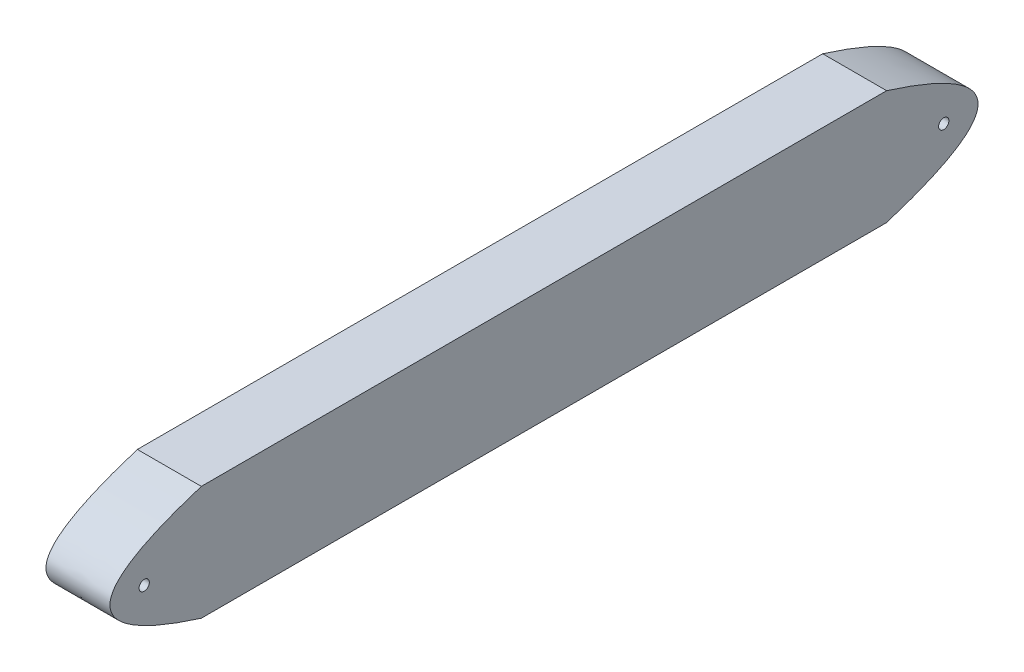
SolidWorks part; units mm, degrees
ref_plane "Front Plane" through (0, 0, 0) normal (0, 0, 1) x (1, 0, 0)
ref_plane "Top Plane" through (0, 0, 0) normal (0, 1, 0) x (1, 0, 0)
ref_plane "Right Plane" through (0, 0, 0) normal (1, 0, 0) x (0, 0, -1)
sketch "Sketch1" plane through (0, 0, 0) normal (1, 0, 0) x (0, 0, -1)
  line L0 (-150, 25) -> (150, 25)
  line L1 (-150, -25) -> (150, -25)
  circle A0 centre (-175, 0) radius 2.25
  circle A1 centre (175, 0) radius 2.25
  spline S0 degree 2 poles (150, 25) (230, 0) (150, -25) knots 0 0 0 1 1 1
  spline S1 degree 2 poles (-150, 25) (-230, 0) (-150, -25) knots 0 0 0 1 1 1
  dimension "D8" = 4.5
  dimension "D10" = 4.5
  dimension "D1" = 300
  dimension "D2" = 50
  dimension "D3" = 25
  dimension "D4" = 40
  dimension "D5" = 40
  dimension "D6" = 15
  dimension "D7" = 0
  dimension "D9" = 15
extrude "Boss-Extrude1" add sketch "Sketch1" along normal blind 28
